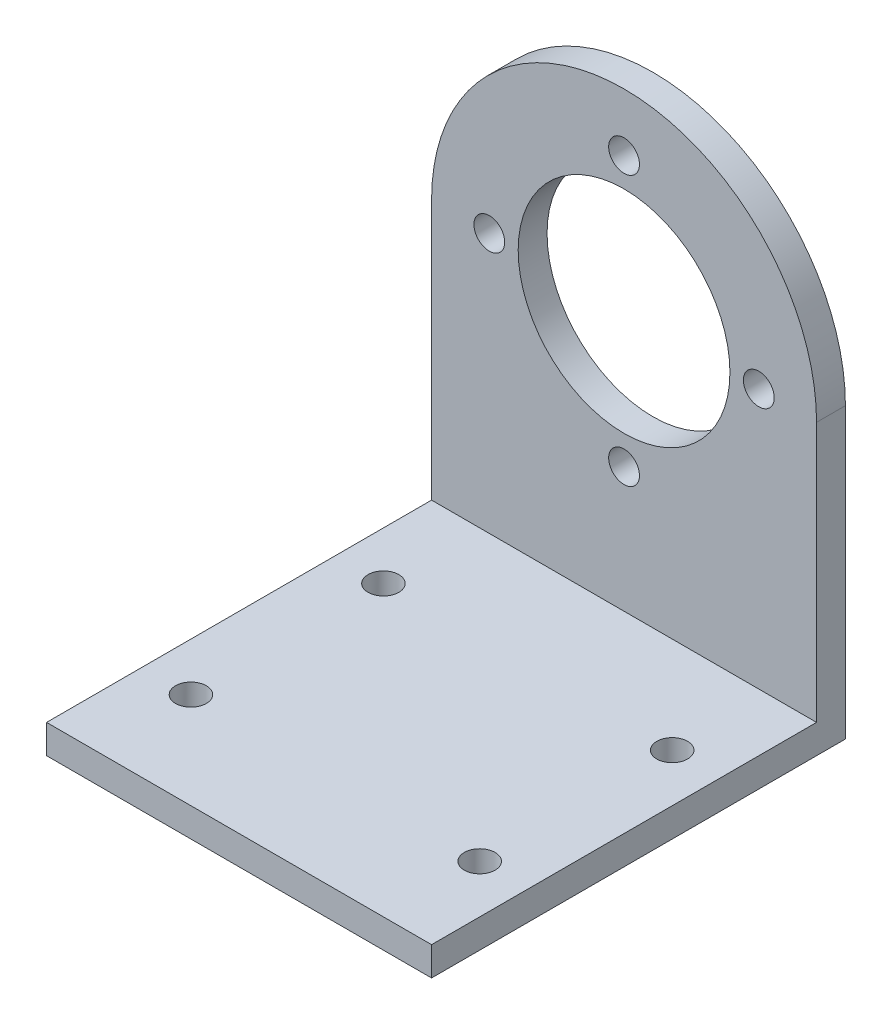
SolidWorks part; units mm, degrees
ref_plane "前视基准面" through (0, 0, 0) normal (0, 0, 1) x (1, 0, 0)
ref_plane "上视基准面" through (0, 0, 0) normal (0, 1, 0) x (1, 0, 0)
ref_plane "右视基准面" through (0, 0, 0) normal (1, 0, 0) x (0, 0, -1)
sketch "草图1" plane through (0, 0, 0) normal (0, 0, 1) x (1, 0, 0)
  line L0 (-20, 13.5) -> (20, 13.5)
  line L1 (20, -13.5) -> (-20, -13.5)
  line L2 (20, -13.5) -> (20, 13.5)
  line L4 (-20, -13.5) -> (-20, 13.5)
  line L5 (20, -13.5) -> (-20, 13.5) construction
  line L6 (20, 13.5) -> (-20, -13.5) construction
  point P0 (0, 0)
  dimension "D1" = 40
  dimension "D2" = 27
extrude "凸台-拉伸1" add sketch "草图1" along normal blind 3
sketch "草图2" plane through (0, 0, 0) normal (0, 0, -1) x (-1, 0, 0)
  line L0 (-20, 13.5) -> (20, 13.5) construction
  line L1 (20, 13.5) -> (20, -13.5) construction
  line L2 (-20, 13.5) -> (20, 13.5)
  arc A0 (-20, 13.5) -> (20, 13.5) centre (0, 13.5) cw
extrude "凸台-拉伸2" add sketch "草图2" against normal blind 3
sketch "草图3" plane through (0, -13.5, 0) normal (0, -1, 0) x (1, 0, 0)
  line L1 (20, 0) -> (-20, 0)
  line L2 (20, 0) -> (20, 43)
  line L3 (20, 43) -> (-20, 43)
  line L4 (-20, 0) -> (-20, 43)
  dimension "D1" = 43
  dimension "D2" = 40
extrude "凸台-拉伸3" add sketch "草图3" along normal blind 3
sketch "草图5" plane through (0, 0, 0) normal (0, 0, -1) x (-1, 0, 0)
  line L3 (20, -16.5) -> (20, 13.5)
  line L4 (-20, 13.5) -> (-20, -16.5)
  line L5 (-20, -16.5) -> (20, -16.5)
  line L6 (20, -16.5) -> (20, 13.5)
  line L7 (-20, 13.5) -> (-20, -16.5)
  line L8 (-20, -16.5) -> (20, -16.5)
  circle A0 centre (0, 13.5) radius 11
  arc A1 (20, 13.5) -> (-20, 13.5) centre (0, 13.5) ccw
  arc A2 (20, 13.5) -> (-20, 13.5) centre (0, 13.5) ccw
  dimension "D2" = 22
  dimension "D1" = 0
extrude "切除-拉伸1" cut sketch "草图5" against normal through all contours A0
sketch "草图6" plane through (0, 0, 0) normal (0, 0, -1) x (-1, 0, 0)
  circle A0 centre (0, 27.5) radius 1.6
  circle A1 centre (0, 13.5) radius 11 construction
  arc A3 (20, 13.5) -> (-20, 13.5) centre (0, 13.5) ccw construction
  dimension "D1" = 3.2
  dimension "D3" = 14
  dimension "D2" = 14
extrude "切除-拉伸2" cut sketch "草图6" against normal through all
pattern_circular "阵列(圆周)1" count 4 every 90 about axis through (0, 13.5, 0) along (0, 0, 1) of "切除-拉伸2"
sketch "草图7" plane through (0, -16.5, 0) normal (0, -1, 0) x (1, 0, 0)
  line L0 (20, 0) -> (20, 43) construction
  line L1 (20, 43) -> (-20, 43) construction
  circle A0 centre (15, 33) radius 1.6
  dimension "D1" = 3.2
  dimension "D2" = 5
  dimension "D3" = 10
extrude "切除-拉伸3" cut sketch "草图7" against normal through all
pattern_linear "阵列(线性)1" count 2 spacing 20 along (0, 0, -1) of "切除-拉伸3"
ref_plane "基准面4" through (0, 0, 0) normal (1, 0, 0) x (0, 0, -1)
mirror "镜向1" about plane through (0, 0, 0) normal (1, 0, 0) of "阵列(线性)1", "切除-拉伸3"
